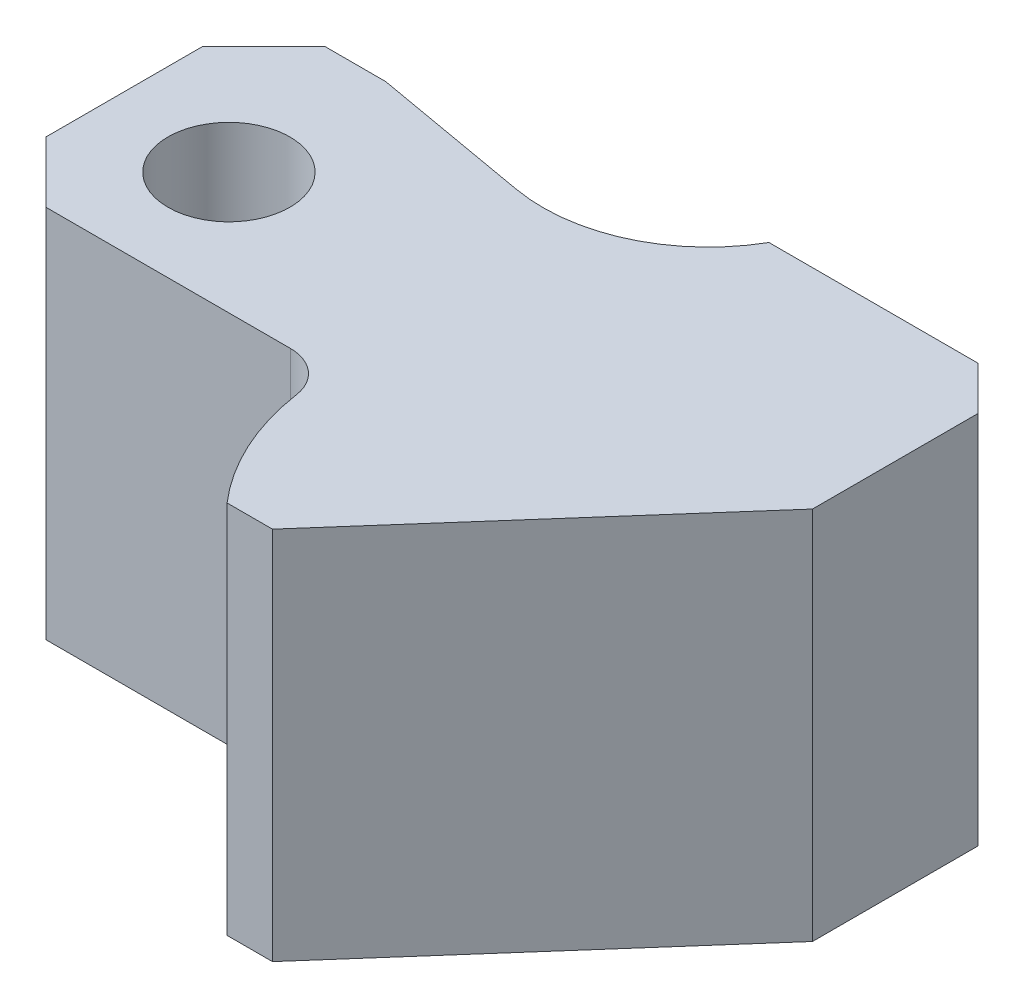
SolidWorks part; units mm, degrees
material "AISI 1020"
ref_plane "Front Plane" through (0, 0, 0) normal (0, 0, 1) x (1, 0, 0)
ref_plane "Top Plane" through (0, 0, 0) normal (0, 1, 0) x (1, 0, 0)
ref_plane "Right Plane" through (0, 0, 0) normal (1, 0, 0) x (0, 0, -1)
sketch "Sketch2" plane through (0, 0, 0) normal (0, 1, 0) x (1, 0, 0)
  line L0 (-7, 18) -> (0, 18)
  line L1 (-7, -14) -> (21.0666, -14)
  line L2 (-14, -7) -> (-14, 11)
  line L3 (-14, -7) -> (-7, -14)
  line L4 (0, 18) -> (18.2431, 14.7833)
  line L5 (-14, 11) -> (-7, 18)
  line L6 (38, 24) -> (62, 24)
  line L7 (62, 24) -> (67, 19)
  line L8 (67, 19) -> (67, 0)
  line L9 (67, 0) -> (38, -33)
  line L10 (38, -33) -> (32.7881, -33)
  circle A0 centre (0, 0) radius 7
  arc A1 (18.2431, 14.7833) -> (38, 24) centre (21.5424, 33.4946) ccw
  arc A2 (26.0123, -18.2647) -> (32.7881, -33) centre (54.697, -14) ccw
  arc A3 (26.0123, -18.2647) -> (21.0666, -14) centre (21.0666, -19) ccw
  point P14 (22.7213, -14.1543)
  dimension "D1" = 14
  dimension "D11" = 38
  dimension "D17" = 58
  dimension "D21" = 10
  dimension "D2" = 7
  dimension "D3" = 7
  dimension "D4" = 32
  dimension "D5" = 45
  dimension "D6" = 45
  dimension "D7" = 14
  dimension "D8" = 14
  dimension "D9" = 14
  dimension "D10" = 10
  dimension "D13" = 5
  dimension "D15" = 24
  dimension "D14" = 45
  dimension "D18" = 81
  dimension "D16" = 57
  dimension "D19" = 19
  dimension "D20" = 29
  dimension "D22" = 19
  dimension "D12" = 29
extrude "Boss-Extrude2" add sketch "Sketch2" along normal mid plane 43
equation "\"A\"= 81"
equation "\"B\"= 57"
equation "\"C\"= 43"
equation "\"D18@Sketch2\"=\"A\""
equation "\"D16@Sketch2\"=\"B\""
equation "\"D1@Boss-Extrude2\"=\"C\""
